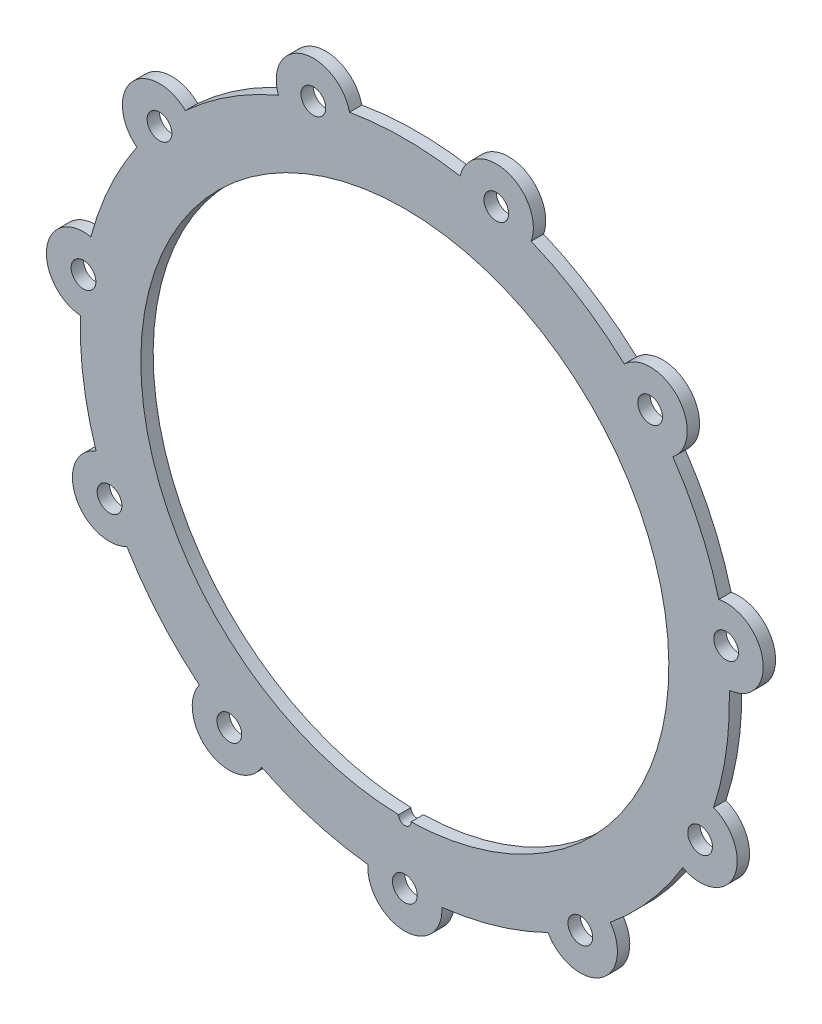
SolidWorks part; units mm, degrees
ref_plane "前视基准面" through (0, 0, 0) normal (0, 0, 1) x (1, 0, 0)
ref_plane "上视基准面" through (0, 0, 0) normal (0, 1, 0) x (1, 0, 0)
ref_plane "右视基准面" through (0, 0, 0) normal (1, 0, 0) x (0, 0, -1)
sketch "草图1" plane through (0, 0, 0) normal (0, 0, 1) x (1, 0, 0)
  line L0 (-12.7971, -30.8803) -> (-64.7628, -23.4088) construction
  line L1 (-64.7628, -23.4088) -> (-86.4682, -20.288) construction
  line L2 (-12.7971, -30.8803) -> (-60.5528, -52.6896) construction
  line L3 (-60.5528, -52.6896) -> (-72.1459, -57.984) construction
  circle A42 centre (-12.7971, -30.8803) radius 42.7
  circle A43 centre (-12.7971, -30.8803) radius 62.5 construction
  circle A44 centre (-12.7971, -30.8803) radius 59 construction
  circle A45 centre (-12.7971, -30.8803) radius 52.5 construction
  circle A46 centre (-64.7628, -23.4088) radius 2
  circle A47 centre (-60.5528, -52.6896) radius 6 construction
  circle A48 centre (-64.7628, -23.4088) radius 6 construction
  arc A49 (-70.7017, -22.5549) -> (-65.2759, -29.3868) centre (-64.7628, -23.4088) ccw
  arc A50 (-62.7294, -47.0983) -> (-66.0106, -55.1821) centre (-60.5528, -52.6896) ccw
  arc A51 (-62.7294, -47.0983) -> (-65.2759, -29.3868) centre (-12.7971, -30.8803) cw
  arc A52 (-57.0085, 7.429) -> (-56.1376, -1.2518) centre (-52.474, 3.4999) ccw
  arc A53 (-63.5709, -17.5284) -> (-56.1376, -1.2518) centre (-12.7971, -30.8803) cw
  arc A54 (-63.5709, -17.5284) -> (-70.7017, -22.5549) centre (-64.7628, -23.4088) ccw
  circle A55 centre (-52.474, 3.4999) radius 2
  arc A56 (-29.2785, 25.25) -> (-33.2391, 17.4764) centre (-27.5881, 19.493) ccw
  arc A57 (-48.2921, 7.8024) -> (-33.2391, 17.4764) centre (-12.7971, -30.8803) cw
  arc A58 (-48.2921, 7.8024) -> (-57.0085, 7.429) centre (-52.474, 3.4999) ccw
  circle A59 centre (-27.5881, 19.493) radius 2
  arc A60 (3.6842, 25.25) -> (-3.8503, 20.8517) centre (1.9938, 19.493) ccw
  arc A61 (-21.744, 20.8517) -> (-3.8503, 20.8517) centre (-12.7971, -30.8803) cw
  arc A62 (-21.744, 20.8517) -> (-29.2785, 25.25) centre (-27.5881, 19.493) ccw
  circle A63 centre (1.9938, 19.493) radius 2
  arc A64 (31.4142, 7.429) -> (22.6979, 7.8024) centre (26.8797, 3.4999) ccw
  arc A65 (7.6448, 17.4764) -> (22.6979, 7.8024) centre (-12.7971, -30.8803) cw
  arc A66 (7.6448, 17.4764) -> (3.6842, 25.25) centre (1.9938, 19.493) ccw
  circle A67 centre (26.8797, 3.4999) radius 2
  arc A68 (45.1074, -22.5549) -> (37.9766, -17.5284) centre (39.1685, -23.4088) ccw
  arc A69 (30.5433, -1.2518) -> (37.9766, -17.5284) centre (-12.7971, -30.8803) cw
  arc A70 (30.5433, -1.2518) -> (31.4142, 7.429) centre (26.8797, 3.4999) ccw
  circle A71 centre (39.1685, -23.4088) radius 2
  arc A72 (40.4163, -55.1821) -> (37.1351, -47.0983) centre (34.9585, -52.6896) ccw
  arc A73 (39.6816, -29.3868) -> (37.1351, -47.0983) centre (-12.7971, -30.8803) cw
  arc A74 (39.6816, -29.3868) -> (45.1074, -22.5549) centre (39.1685, -23.4088) ccw
  circle A75 centre (34.9585, -52.6896) radius 2
  arc A76 (18.8303, -80.0937) -> (20.4404, -71.5192) centre (15.5865, -75.0461) ccw
  arc A77 (32.1582, -57.9961) -> (20.4404, -71.5192) centre (-12.7971, -30.8803) cw
  circle A78 centre (-60.5528, -52.6896) radius 2 construction
  arc A79 (32.1582, -57.9961) -> (40.4163, -55.1821) centre (34.9585, -52.6896) ccw
  circle A80 centre (15.5865, -75.0461) radius 2
  arc A81 (-12.7971, -89.3803) -> (-6.8069, -83.0375) centre (-12.7971, -83.3803) ccw
  arc A82 (10.3619, -77.9963) -> (-6.8069, -83.0375) centre (-12.7971, -30.8803) cw
  arc A83 (10.3619, -77.9963) -> (18.8303, -80.0937) centre (15.5865, -75.0461) ccw
  circle A84 centre (-12.7971, -83.3803) radius 2
  arc A85 (-44.4246, -80.0937) -> (-35.9562, -77.9963) centre (-41.1808, -75.0461) ccw
  arc A86 (-18.7873, -83.0375) -> (-35.9562, -77.9963) centre (-12.7971, -30.8803) cw
  arc A87 (-18.7873, -83.0375) -> (-12.7971, -89.3803) centre (-12.7971, -83.3803) ccw
  circle A88 centre (-41.1808, -75.0461) radius 2
  arc A89 (-66.0106, -55.1821) -> (-57.7525, -57.9961) centre (-60.5528, -52.6896) ccw
  arc A90 (-46.0347, -71.5192) -> (-57.7525, -57.9961) centre (-12.7971, -30.8803) cw
  arc A91 (-46.0347, -71.5192) -> (-44.4246, -80.0937) centre (-41.1808, -75.0461) ccw
  circle A92 centre (-60.5528, -52.6896) radius 2
  dimension "D1" = 118
  dimension "D2" = 105
  dimension "D3" = 85.4
extrude "凸台-拉伸1" add sketch "草图1" along normal blind 2
sketch "草图2" plane through (0, 0, 2) normal (0, 0, 1) x (1, 0, 0)
  circle A1 centre (-12.7971, -30.8803) radius 42.7 construction
  circle A2 centre (-12.7971, -73.5803) radius 1
extrude "切除-拉伸1" cut sketch "草图2" against normal blind 2
equation "\"52.5×2\"=96.9638"
